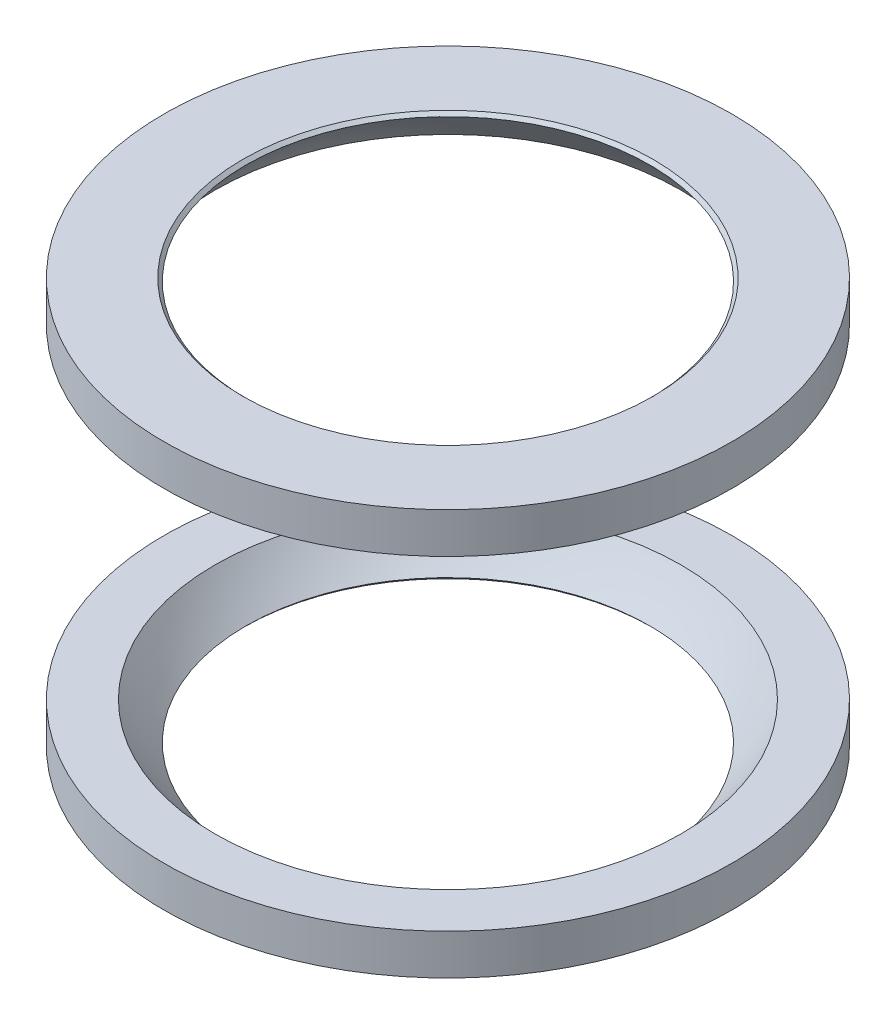
SolidWorks part; units mm, degrees
material "Chrome Stainless Steel"
ref_plane "Front Plane" through (0, 0, 0) normal (0, 0, 1) x (1, 0, 0)
ref_plane "Top Plane" through (0, 0, 0) normal (0, 1, 0) x (1, 0, 0)
ref_plane "Right Plane" through (0, 0, 0) normal (1, 0, 0) x (0, 0, -1)
sketch "Sketch1" plane through (0, 0, 0) normal (0, 1, 0) x (1, 0, 0)
  circle A0 centre (0, 0) radius 11.1125
extrude "Boss-Extrude1" add sketch "Sketch1" along normal blind 19.05
sketch "Sketch2" plane through (0, 19.05, 0) normal (0, 1, 0) x (1, 0, 0)
  circle A0 centre (0, 0) radius 6.35
extrude "Cut-Extrude1" cut sketch "Sketch2" against normal through all
sketch "Sketch3" plane through (0, 0, 0) normal (0, 0, 1) x (1, 0, 0)
  line L0 (0, 20.6375) -> (0, -1.5875)
  line L1 (0, 23.0667) -> (0, -4.3) construction
  arc A0 (0, 20.6375) -> (0, -1.5875) centre (0, 9.525) ccw
revolve "Cut-Revolve1" cut sketch "Sketch3" angle 360 about L1
sketch "Sketch4" plane through (0, 0, 0) normal (0, 0, 1) x (1, 0, 0)
  line L0 (-11.1125, 9.525) -> (11.1125, 9.525) construction
  line L1 (-15.2622, 3.175) -> (15.2622, 3.175)
  line L2 (-15.2622, 3.175) -> (-15.2622, 15.875)
  line L3 (-15.2622, 15.875) -> (15.2622, 15.875)
  line L4 (15.2622, 3.175) -> (15.2622, 15.875)
  line L5 (-15.2622, 3.175) -> (15.2622, 15.875) construction
  line L6 (-15.2622, 15.875) -> (15.2622, 3.175) construction
  point P0 (0, 9.525)
extrude "Cut-Extrude2" cut sketch "Sketch4" against normal mid plane 50.8
sketch "Sketch5" plane through (0, 0, 0) normal (0, 0, 1) x (1, 0, 0)
  line L0 (-11.1125, 19.05) -> (11.1125, 19.05)
  line L1 (11.1125, 19.05) -> (11.1125, 17.4625)
  line L2 (11.1125, 15.875) -> (11.1125, 19.05) construction
  line L3 (11.1125, 17.4625) -> (-11.1125, 17.4625)
  line L4 (-11.1125, 19.05) -> (-11.1125, 15.875) construction
  line L5 (-11.1125, 17.4625) -> (-11.1125, 19.05)
  line L6 (-11.1125, 0) -> (11.1125, 0)
  line L7 (11.1125, 0) -> (11.1125, 1.5875)
  line L8 (11.1125, 0) -> (11.1125, 3.175) construction
  line L9 (11.1125, 1.5875) -> (-11.1125, 1.5875)
  line L10 (-11.1125, 3.175) -> (-11.1125, 0) construction
  line L11 (-11.1125, 1.5875) -> (-11.1125, 0)
extrude "Cut-Extrude3" cut sketch "Sketch5" against normal mid plane 50.8
chamfer "Chamfer2" distance 0.254 angle 45 1 edges at (0, 17.4625, -7.7771)
chamfer "Chamfer3" distance 0.254 angle 45 1 edges at (-7.7771, 1.5875, 0)
